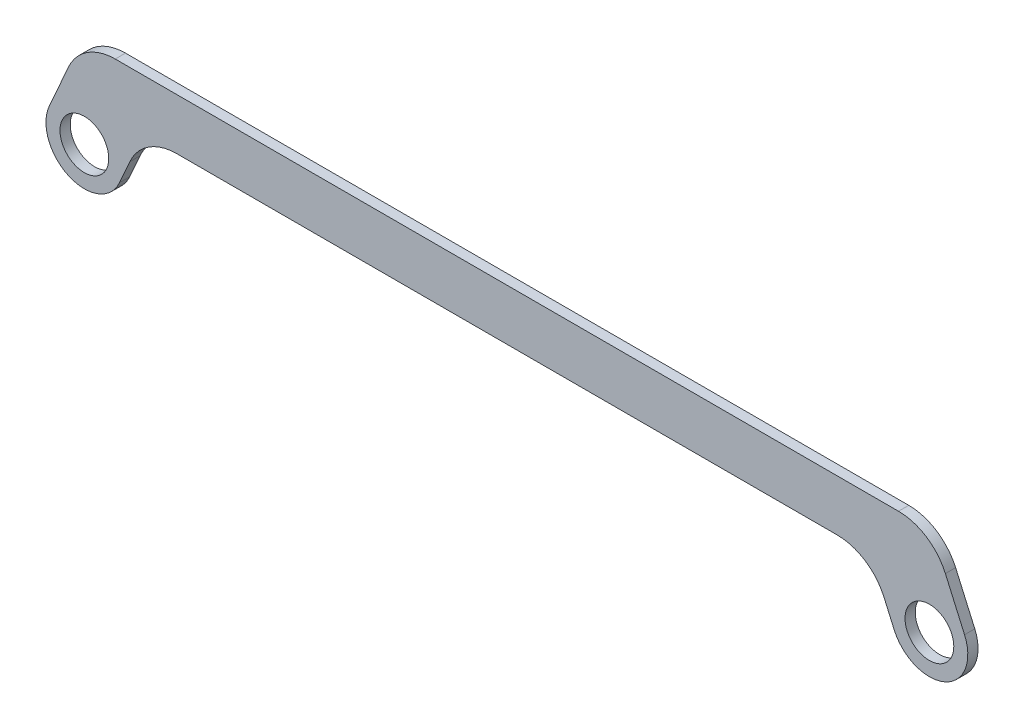
SolidWorks part; units mm, degrees
ref_plane "前视基准面" through (0, 0, 0) normal (0, 0, 1) x (1, 0, 0)
ref_plane "上视基准面" through (0, 0, 0) normal (0, 1, 0) x (1, 0, 0)
ref_plane "右视基准面" through (0, 0, 0) normal (1, 0, 0) x (0, 0, -1)
sketch "草图1" plane through (0, 0, 0) normal (0, 0, 1) x (1, 0, 0)
  line L28 (0, 0) -> (330, 0) construction
  line L31 (-0.9801, 34.9353) -> (330.9801, 34.9353)
  line L32 (22.9856, 14.9353) -> (307.0144, 14.9353)
  line L33 (13.7234, -6.0555) -> (22.9856, 14.9353)
  line L34 (-13.7234, 6.0555) -> (-0.9801, 34.9353)
  line L35 (165, 0) -> (165, -17.6097) construction
  line L36 (316.2766, -6.0555) -> (307.0144, 14.9353)
  line L37 (343.7234, 6.0555) -> (330.9801, 34.9353)
  circle A24 centre (0, 0) radius 15 construction
  circle A25 centre (0, 0) radius 9.525
  circle A26 centre (330, 0) radius 9.525
  circle A27 centre (330, 0) radius 15 construction
  arc A30 (13.7234, -6.0555) -> (-13.7234, 6.0555) centre (0, 0) cw
  arc A31 (316.2766, -6.0555) -> (343.7234, 6.0555) centre (330, 0) ccw
  dimension "D1" = 19.05
  dimension "D3" = 330
  dimension "D4" = 20
  dimension "D2" = 30
extrude "凸台-拉伸1" add sketch "草图1" along normal blind 4
fillet "圆角1" radius 20 4 edges at (307.0144, 14.9353, 2) (330.9801, 34.9353, 2) (22.9856, 14.9353, 2) (-0.9801, 34.9353, 2)
